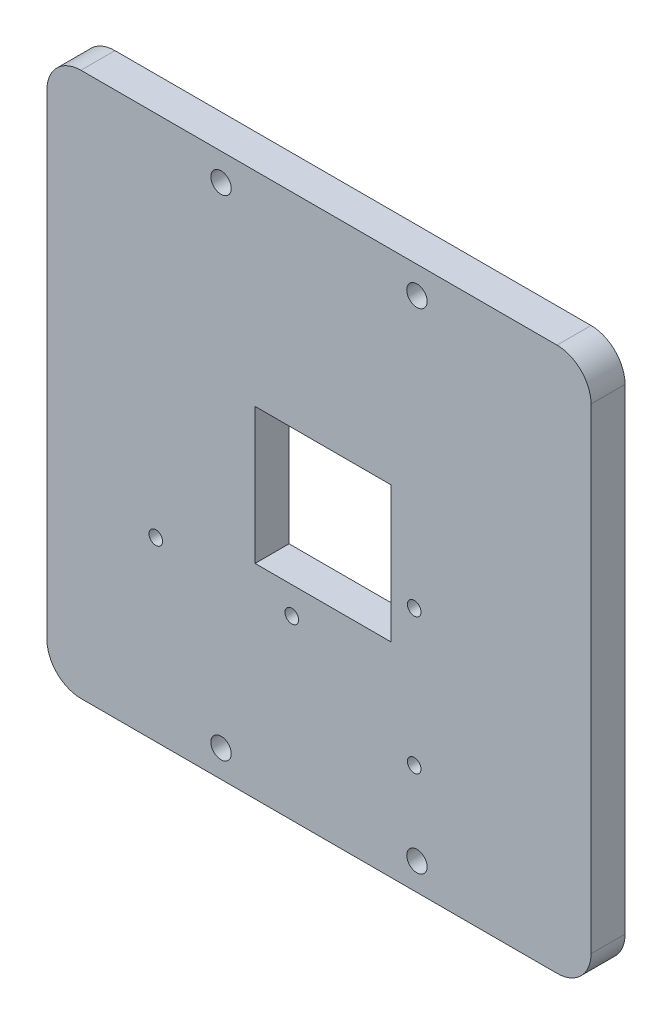
SolidWorks part; units mm, degrees
ref_plane "Plan de face" through (0, 0, 0) normal (0, 0, 1) x (1, 0, 0)
ref_plane "Plan de dessus" through (0, 0, 0) normal (0, 1, 0) x (1, 0, 0)
ref_plane "Plan de droite" through (0, 0, 0) normal (1, 0, 0) x (0, 0, -1)
sketch "Esquisse1" plane through (0, 0, 0) normal (0, 0, 1) x (1, 0, 0)
  line L0 (40, 50) -> (40, 80)
  line L1 (5, 0) -> (40, 0)
  line L2 (0, 5) -> (0, 75)
  line L3 (5, 80) -> (40, 80)
  line L4 (40, 0) -> (40, 30)
  line L9 (40, 50) -> (40, 30)
  circle A0 centre (25.6, 76) radius 1.5
  circle A1 centre (25.6, 4) radius 1.5
  arc A2 (5, 0) -> (0, 5) centre (5, 5) cw
  arc A3 (0, 75) -> (5, 80) centre (5, 75) cw
  point P9 (40, 40)
  point P16 (0, 0)
  point P19 (0, 80)
  dimension "D3" = 3
  dimension "D4" = 3
  dimension "D9" = 5
  dimension "D1" = 80
  dimension "D2" = 40
  dimension "D5" = 4
  dimension "D6" = 4
  dimension "D7" = 14.4
  dimension "D8" = 14.4
extrude "Boss.-Extru.1" add sketch "Esquisse1" along normal blind 5
mirror "Symétrie1" about plane through (40, 50, 5) normal (-1, 0, 0) of "Boss.-Extru.1"
sketch "Esquisse2" plane through (0, 0, 5) normal (0, 0, 1) x (1, 0, 0)
  line L0 (75, 80) -> (5, 80) construction
  line L1 (30.6, 50) -> (50.6, 50)
  line L2 (30.6, 50) -> (30.6, 30)
  line L3 (30.6, 30) -> (50.6, 30)
  line L4 (50.6, 50) -> (50.6, 30)
  line L5 (80, 75) -> (80, 5) construction
  dimension "D1" = 20
  dimension "D2" = 30
  dimension "D3" = 29.4
  dimension "D4" = 20
extrude "Enlèv. mat.-Extru.1" cut sketch "Esquisse2" against normal through all
sketch "Esquisse3" plane through (0, 0, 5) normal (0, 0, 1) x (1, 0, 0)
  circle A0 centre (54, 36) radius 1
  circle A1 centre (54, 16) radius 1
  circle A2 centre (36, 26) radius 1
  circle A3 centre (16, 26) radius 1
  dimension "D1" = 2
  dimension "D2" = 2
  dimension "D3" = 2
  dimension "D4" = 2
extrude "Enlèv. mat.-Extru.2" cut sketch "Esquisse3" against normal through all
